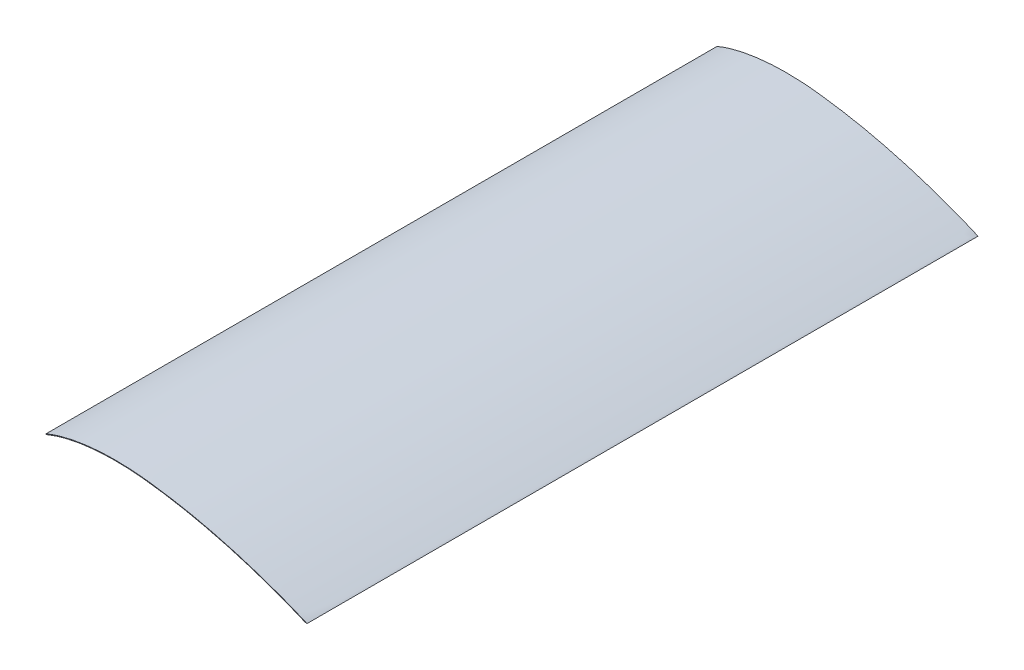
SolidWorks part; units mm, degrees
ref_plane "Front Plane" through (0, 0, 0) normal (0, 0, 1) x (1, 0, 0)
ref_plane "Top Plane" through (0, 0, 0) normal (0, 1, 0) x (1, 0, 0)
ref_plane "Right Plane" through (0, 0, 0) normal (1, 0, 0) x (0, 0, -1)
sketch "Sketch1" plane through (0, 0, 0) normal (0, 0, 1) x (1, 0, 0)
  line L0 (1922.7474, 3204.3479) -> (1922.4911, 3205.0669)
  line L1 (2268.0252, 3160.2572) -> (2270.7779, 3159.8966)
  spline S0 degree 3 poles (2270.7779, 3159.8966) (2270.7544, 3159.9114) (2270.637, 3159.9624) (2270.3658, 3160.0693) (2269.9391, 3160.2631) (2269.327, 3160.5007) (2268.5717, 3160.862) (2267.6094, 3161.2469) (2266.5027, 3161.7511) (2265.2, 3162.2638) (2263.7583, 3162.9092) (2262.1211, 3163.5642) (2260.3357, 3164.3302) (2258.3641, 3165.1272) (2256.2608, 3166.0357) (2253.9631, 3166.9125) (2251.5439, 3167.9271) (2248.9374, 3168.9369) (2246.1985, 3170.0895) (2243.2663, 3171.2014) (2240.1994, 3172.3768) (2237.0026, 3173.6307) (2233.6251, 3174.838) (2230.138, 3176.1781) (2226.5013, 3177.5111) (2222.7231, 3178.8466) (2218.8043, 3180.2326) (2214.7659, 3181.6845) (2210.5736, 3183.0661) (2206.2868, 3184.5406) (2201.8622, 3185.9907) (2197.319, 3187.4637) (2192.6742, 3188.9341) (2187.9232, 3190.4276) (2183.0736, 3191.9193) (2178.1023, 3193.3734) (2173.0553, 3194.8511) (2167.9082, 3196.2771) (2162.6816, 3197.7233) (2157.3882, 3199.1845) (2151.9869, 3200.5525) (2146.5304, 3201.9292) (2141.0237, 3203.3399) (2135.4475, 3204.6465) (2129.8257, 3205.9359) (2124.134, 3207.1756) (2118.4178, 3208.4505) (2112.6463, 3209.6173) (2106.8584, 3210.7869) (2101.0263, 3211.8315) (2095.1981, 3212.9334) (2089.3451, 3213.9416) (2083.4792, 3214.8366) (2077.6195, 3215.8199) (2071.7427, 3216.5838) (2065.898, 3217.4507) (2060.0556, 3218.1264) (2054.217, 3218.7992) (2048.365, 3219.4484) (2042.5017, 3219.9687) (2036.6552, 3220.3646) (2030.842, 3220.7138) (2025.0817, 3220.9151) (2019.3779, 3221.0696) (2013.7535, 3221.0777) (2008.1838, 3221.0335) (2002.7072, 3220.8533) (1997.3109, 3220.5973) (1992.0081, 3220.2608) (1986.7979, 3219.8528) (1981.6945, 3219.3503) (1976.7082, 3218.7736) (1971.8443, 3218.1037) (1967.094, 3217.4011) (1962.476, 3216.6153) (1957.995, 3215.7308) (1953.6538, 3214.8118) (1949.4595, 3213.8385) (1945.4178, 3212.8354) (1941.5394, 3211.737) (1937.7862, 3210.7018) (1934.2243, 3209.5201) (1930.8235, 3208.3387) (1927.5775, 3207.1754) (1924.8324, 3206.0424) (1923.1518, 3205.3482) (1922.4911, 3205.0669) knots 0 0 0 0 0.003265 0.015304 0.034284 0.058758 0.092936 0.133106 0.181131 0.236534 0.298408 0.367661 0.444765 0.52787 0.618825 0.715328 0.818287 0.92864 1.045449 1.169214 1.29899 1.433381 1.574768 1.722581 1.874597 2.032229 2.19588 2.365548 2.539067 2.717193 2.900973 3.089002 3.281284 3.476406 3.677213 3.880546 4.088159 4.298328 4.511358 4.728683 4.946893 5.169412 5.393369 5.61827 5.845824 6.074602 6.306269 6.53753 6.770051 7.003674 7.237297 7.470609 7.705102 7.93814 8.172291 8.404986 8.635962 8.866868 9.099173 9.331354 9.562034 9.791273 10.01915 10.242764 10.465163 10.683408 10.900595 11.112295 11.321462 11.528149 11.729529 11.927109 12.12096 12.309407 12.494251 12.674163 12.848839 13.018332 13.182697 13.34062 13.49442 13.64245 13.783738 13.919675 14.049615 14.134429 14.134429 14.134429 14.134429
  spline S1 degree 3 poles (2268.0252, 3160.2572) (2267.5129, 3160.4836) (2266.9632, 3160.7088) (2265.8236, 3161.2041) (2265.1724, 3161.4565) (2263.8827, 3162.0127) (2263.264, 3162.2805) (2261.2846, 3163.0904) (2259.9503, 3163.6565) (2257.2586, 3164.7671) (2255.9447, 3165.3286) (2253.243, 3166.3885) (2251.9009, 3166.954) (2249.215, 3168.0204) (2247.8544, 3168.5749) (2245.1842, 3169.6622) (2243.8367, 3170.1697) (2239.6842, 3171.7559) (2236.9169, 3172.834) (2231.286, 3174.8977) (2228.5043, 3175.9767) (2222.8834, 3177.99) (2220.0541, 3178.9823) (2211.4958, 3182.0336) (2205.7095, 3183.9408) (2194.1065, 3187.7038) (2188.291, 3189.5527) (2176.6172, 3193.0413) (2170.7473, 3194.7012) (2160.0464, 3197.6614) (2155.2312, 3198.9458) (2145.5352, 3201.3961) (2140.7024, 3202.6385) (2130.9694, 3204.9005) (2126.086, 3205.9734) (2116.3277, 3208.1189) (2111.4319, 3209.1207) (2101.6339, 3210.9811) (2096.7077, 3211.9027) (2086.8724, 3213.5823) (2081.9226, 3214.3863) (2072.8808, 3215.7044) (2068.7305, 3216.2977) (2060.4726, 3217.3377) (2056.3143, 3217.7991) (2048.0247, 3218.7161) (2043.8833, 3219.0984) (2035.5685, 3219.6797) (2031.41, 3219.9269) (2019.3811, 3220.3514) (2011.5151, 3220.4094) (1989.641, 3219.5884) (1975.6281, 3218.2937) (1948.5128, 3213.1955) (1935.2508, 3209.6697) (1922.7895, 3204.3658) (1922.7755, 3204.3598) (1922.7614, 3204.3539) (1922.7474, 3204.3479) knots 0.105062 0.105062 0.105062 0.105062 0.17272 0.17272 0.254746 0.254746 0.336772 0.336772 0.507994 0.507994 0.679215 0.679215 0.850436 0.850436 1.021658 1.021658 1.192879 1.192879 1.546135 1.546135 1.899391 1.899391 2.252648 2.252648 2.973527 2.973527 3.694407 3.694407 4.415287 4.415287 5.005866 5.005866 5.596445 5.596445 6.187024 6.187024 6.777602 6.777602 7.368181 7.368181 7.95876 7.95876 8.451933 8.451933 8.945106 8.945106 9.438279 9.438279 9.931452 9.931452 10.862582 10.862582 12.522648 12.522648 14.134429 14.134429 14.134429 14.136243 14.136243 14.136243 14.136243
extrude "Boss-Extrude1" add sketch "Sketch1" along normal blind 895.35
